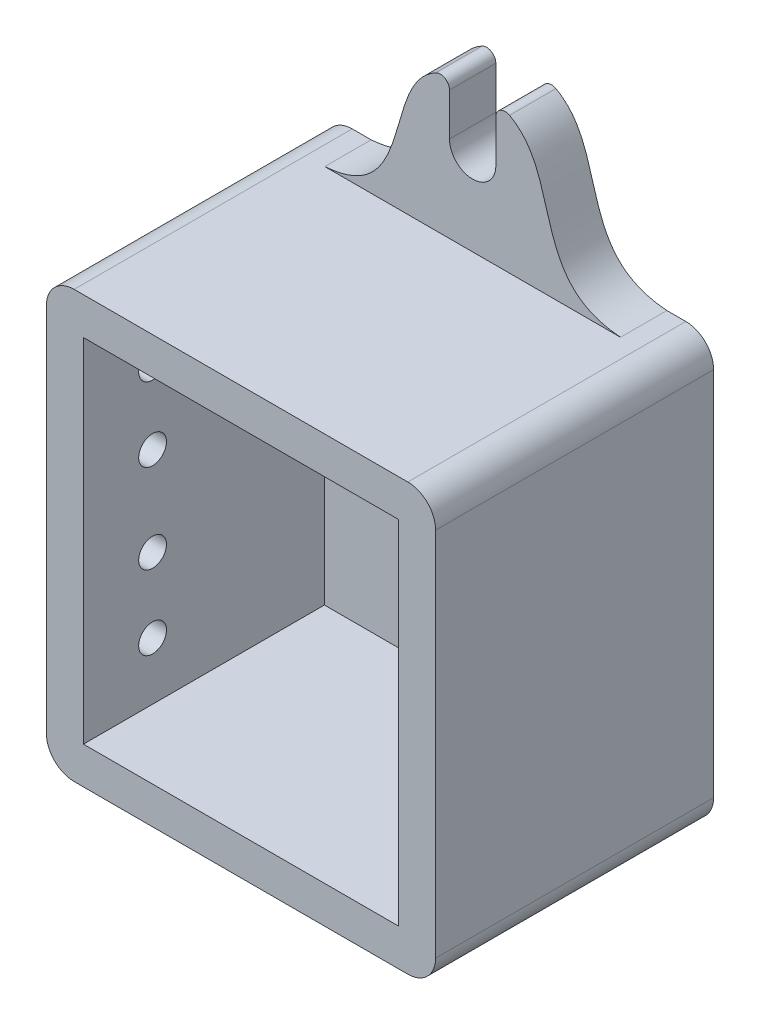
SolidWorks part; units mm, degrees
ref_plane "Piano frontale" through (0, 0, 0) normal (0, 0, 1) x (1, 0, 0)
ref_plane "Piano superiore" through (0, 0, 0) normal (0, 1, 0) x (1, 0, 0)
ref_plane "Piano destro" through (0, 0, 0) normal (1, 0, 0) x (0, 0, -1)
sketch "Schizzo1" plane through (0, 0, 0) normal (0, 0, 1) x (1, 0, 0)
  line L1 (17, -19) -> (-17, -19)
  line L2 (17, -19) -> (17, 19)
  line L3 (17, 19) -> (-17, 19)
  line L4 (-17, -19) -> (-17, 19)
  line L5 (17, -19) -> (-17, 19) construction
  line L6 (17, 19) -> (-17, -19) construction
  point P0 (0, 0)
  dimension "D1" = 34
  dimension "D2" = 38
extrude "Estrusione-Sottile1" add sketch "Schizzo1" along normal blind 30 thin thin type one direction wall 4
sketch "Schizzo2" plane through (0, 0, 0) normal (0, 0, 1) x (1, 0, 0)
  line L1 (21, 23) -> (-21, 23)
  line L2 (21, 23) -> (21, -23)
  line L3 (21, -23) -> (-21, -23)
  line L4 (-21, 23) -> (-21, -23)
  line L5 (21, 23) -> (-21, -23) construction
  line L6 (21, -23) -> (-21, 23) construction
  point P0 (0, 0)
extrude "Estrusione-Estrusione1" add sketch "Schizzo2" along normal blind 4
sketch "Schizzo3" plane through (0, 0, 0) normal (0, 0, 1) x (1, 0, 0)
  line L0 (0, 23) -> (0, 9.6242) construction
  line L1 (0, 0) -> (-17, 0) construction
  line L3 (0, 38.6185) -> (0, 28.7557) construction
  line L4 (21, 23) -> (-21, 23) construction
  line L5 (-15.9566, 23) -> (15.9566, 23)
  line L6 (-17, 19) -> (-17, -19) construction
  line L7 (0, 32.2998) -> (0, 41.2443) construction
  line L8 (-2.5, 32.2998) -> (-2.5, 36.8766)
  line L9 (2.5, 32.2998) -> (2.5, 36.8766)
  line L10 (0, -32.2998) -> (0, -41.2443) construction
  line L11 (0, -38.6185) -> (0, -28.7557) construction
  line L12 (2.5, -32.2998) -> (2.5, -36.8766)
  line L13 (-2.5, -32.2998) -> (-2.5, -36.8766)
  line L14 (-15.9566, -23) -> (15.9566, -23)
  arc A0 (-2.5, 32.2998) -> (2.5, 32.2998) centre (0, 32.2998) ccw
  arc A1 (3.9791, 37.7544) -> (2.5, 36.8766) centre (3.5, 36.8766) ccw
  arc A2 (-3.9791, 37.7544) -> (-2.5, 36.8766) centre (-3.5, 36.8766) cw
  arc A3 (-3.9791, -37.7544) -> (-2.5, -36.8766) centre (-3.5, -36.8766) ccw
  arc A4 (3.9791, -37.7544) -> (2.5, -36.8766) centre (3.5, -36.8766) cw
  arc A5 (-2.5, -32.2998) -> (2.5, -32.2998) centre (0, -32.2998) cw
  spline S0 degree 3 poles (-15.9566, 23) (-8.1141, 23.5658) (-9.022, 32.3292) (-5.1838, 37.0968) (-3.9791, 37.7544) knots 0 0 0 0 0.676225 0.852916 0.852916 0.852916 0.852916
  spline S1 degree 3 poles (15.9566, 23) (8.1141, 23.5658) (9.022, 32.3292) (5.1838, 37.0968) (3.9791, 37.7544) knots 0 0 0 0 0.676225 0.852916 0.852916 0.852916 0.852916
  spline S2 degree 3 poles (15.9566, -23) (8.1141, -23.5658) (9.022, -32.3292) (5.1838, -37.0968) (3.9791, -37.7544) knots 0 0 0 0 0.676225 0.852916 0.852916 0.852916 0.852916
  spline S3 degree 3 poles (-15.9566, -23) (-8.1141, -23.5658) (-9.022, -32.3292) (-5.1838, -37.0968) (-3.9791, -37.7544) knots 0 0 0 0 0.676225 0.852916 0.852916 0.852916 0.852916
  point P15 (0, 36.7721)
  point P46 (0, -36.7721)
  dimension "D1" = 5
  dimension "D2" = 1
sketch "Schizzo4" plane through (-21, 0, 0) normal (-1, 0, 0) x (0, 0, 1)
  line L0 (22.5407, 23) -> (22.5407, -23) construction
  line L1 (30, 23) -> (0, 23) construction
  line L2 (30, -23) -> (0, -23) construction
  line L3 (0, 0) -> (30, 0) construction
  line L4 (0, 23) -> (0, -23) construction
  line L5 (30, 23) -> (30, -23) construction
  circle A0 centre (22.5407, 12.7949) radius 1.5
  circle A1 centre (22.5407, 4.7949) radius 1.5
  circle A2 centre (22.5407, -4.7949) radius 1.5
  circle A3 centre (22.5407, -12.7949) radius 1.5
  dimension "D1" = 3
  dimension "D2" = 8
extrude "Taglio-Estrusione1" cut sketch "Schizzo4" against normal blind 4
fillet "Raccordo1" radius 3 1 edges at (-21, -23, 15)
fillet "Raccordo2" radius 3 1 edges at (21, -23, 15)
fillet "Raccordo3" radius 3 1 edges at (21, 23, 15)
fillet "Raccordo4" radius 3 1 edges at (-21, 23, 15)
sketch "Schizzo5" plane through (0, -23, 0) normal (0, -1, 0) x (1, 0, 0)
  text T0 "<b>   220V</b>\r\n<b>DANGER</b>" font "Swis721 Ex BT" height 6
extrude "Taglio-Estrusione2" [suppressed] cut sketch "Schizzo5" against normal blind 1
extrude "Estrusione-Estrusione3" add sketch "Schizzo3" along normal blind 5
